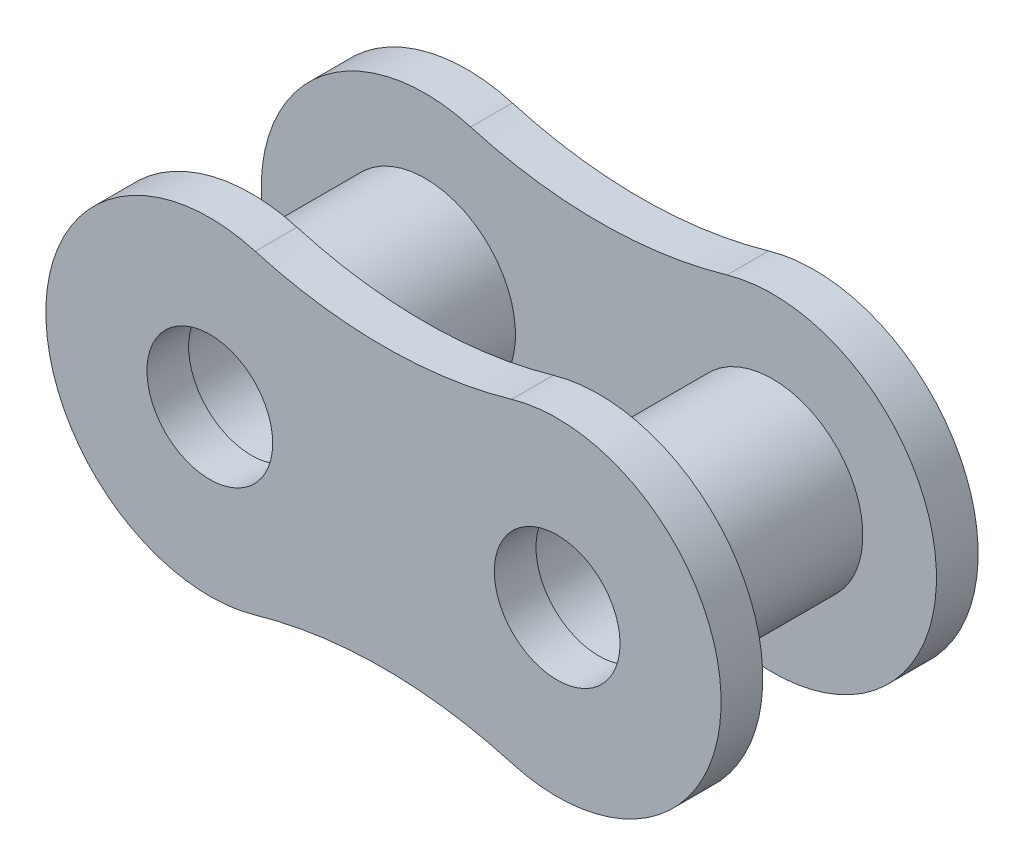
SolidWorks part; units mm, degrees
ref_plane "Front Plane" through (0, 0, 0) normal (0, 0, 1) x (1, 0, 0)
ref_plane "Top Plane" through (0, 0, 0) normal (0, 1, 0) x (1, 0, 0)
ref_plane "Right Plane" through (0, 0, 0) normal (1, 0, 0) x (0, 0, -1)
sketch "Sketch1" plane through (0, 0, 0) normal (0, 0, 1) x (1, 0, 0)
  line L0 (-3.175, 0) -> (3.175, 0) construction
  line L1 (-3.175, 2.9972) -> (-3.175, -2.9972) construction
  line L2 (0, -2.5476) -> (0, 2.5476) construction
  line L3 (3.175, -2.9972) -> (3.175, 2.9972) construction
  circle A0 centre (-3.175, 0) radius 1.651
  circle A1 centre (3.175, 0) radius 1.651
  circle A2 centre (-3.175, 0) radius 1.1493
  circle A3 centre (3.175, 0) radius 1.1493
  arc A4 (-2.3429, 2.8794) -> (-2.3429, -2.8794) centre (-3.175, 0) ccw
  arc A5 (2.3429, -2.8794) -> (2.3429, 2.8794) centre (3.175, 0) ccw
  arc A6 (-2.3429, 2.8794) -> (2.3429, 2.8794) centre (0, 10.9864) ccw
  arc A7 (-2.3429, -2.8794) -> (2.3429, -2.8794) centre (0, -10.9864) cw
  dimension "Roller Dia" = 3.302
  dimension "Pin Dia" = 2.2987
  dimension "Pitch" = 6.35
  dimension "H" = 5.9944
  dimension "D2" = 5.0952
sketch "Sketch2" plane through (0, 0, 0) normal (0, 1, 0) x (1, 0, 0)
  line L0 (0, 1.5875) -> (0, -1.5875) construction
  point P2 (0, -2.3495)
  point P4 (0, 2.3495)
  point P5 (0, 2.4003)
  point P6 (0, 3.1623)
  dimension "W" = 3.175
  dimension "T" = 0.762
  dimension "D1" = 0.762
  dimension "D2" = 0.762
  dimension "D3" = 0.0508
ref_plane "Plane1" through (0, 0, 1.5875) normal (0, 0, 1) x (1, 0, 0)
ref_plane "Plane2" through (0, 0, -2.4003) normal (0, 0, 1) x (1, 0, 0)
sketch "Sketch4" plane through (0, 0, 0) normal (0, 0, 1) x (1, 0, 0)
  circle A0 centre (-3.175, 0) radius 1.651 construction
  circle A1 centre (-3.175, 0) radius 1.651
  circle A2 centre (3.175, 0) radius 1.651 construction
  circle A3 centre (3.175, 0) radius 1.651
  circle A4 centre (-3.175, 0) radius 1.1747
  circle A5 centre (3.175, 0) radius 1.1747
  dimension "D1" = 2.3495
  dimension "D2" = 2.3495
extrude "Boss-Extrude1" add sketch "Sketch4" along normal mid plane 3.175
sketch "Sketch5" plane through (0, 0, 1.5875) normal (0, 0, 1) x (1, 0, 0)
  arc A0 (-2.3429, 2.8794) -> (-2.3429, -2.8794) centre (-3.175, 0) ccw construction
  arc A1 (-2.3429, 2.8794) -> (2.3429, 2.8794) centre (0, 10.9864) ccw construction
  circle A2 centre (-3.175, 0) radius 1.1493 construction
  arc A3 (2.3429, -2.8794) -> (2.3429, 2.8794) centre (3.175, 0) ccw construction
  circle A4 centre (3.175, 0) radius 1.1493 construction
  arc A5 (2.3429, -2.8794) -> (-2.3429, -2.8794) centre (0, -10.9864) ccw construction
  arc A6 (-2.3429, 2.8794) -> (-2.3429, -2.8794) centre (-3.175, 0) ccw
  arc A7 (-2.3429, 2.8794) -> (2.3429, 2.8794) centre (0, 10.9864) ccw
  circle A8 centre (-3.175, 0) radius 1.1493
  arc A9 (2.3429, -2.8794) -> (2.3429, 2.8794) centre (3.175, 0) ccw
  circle A10 centre (3.175, 0) radius 1.1493
  arc A11 (2.3429, -2.8794) -> (-2.3429, -2.8794) centre (0, -10.9864) ccw
extrude "Boss-Extrude2" add sketch "Sketch5" along normal up to vertex (0.762 mm away) separate body up to point (0, 0, 2.3495)
mirror "Mirror3" about plane through (0, 0, 0) normal (0, 0, 1) of bodies 103
combine bodies "Combine2" operation type add bodies to combine 120 103 102 101
equation "\"D2@Sketch1\" =\"H@Sketch1\"*.85"
equation "\"D1@Sketch2\" = \"T@Sketch2\""
equation "\"D1@Sketch4\" = \"Pin Dia@Sketch1\"+.002"
equation "\"D2@Sketch4\" = \"D1@Sketch4\""
equation "\"D1@Boss-Extrude1\" = \"W@Sketch2\""
equation "\"D2@Sketch2\" = \"T@Sketch2\""
